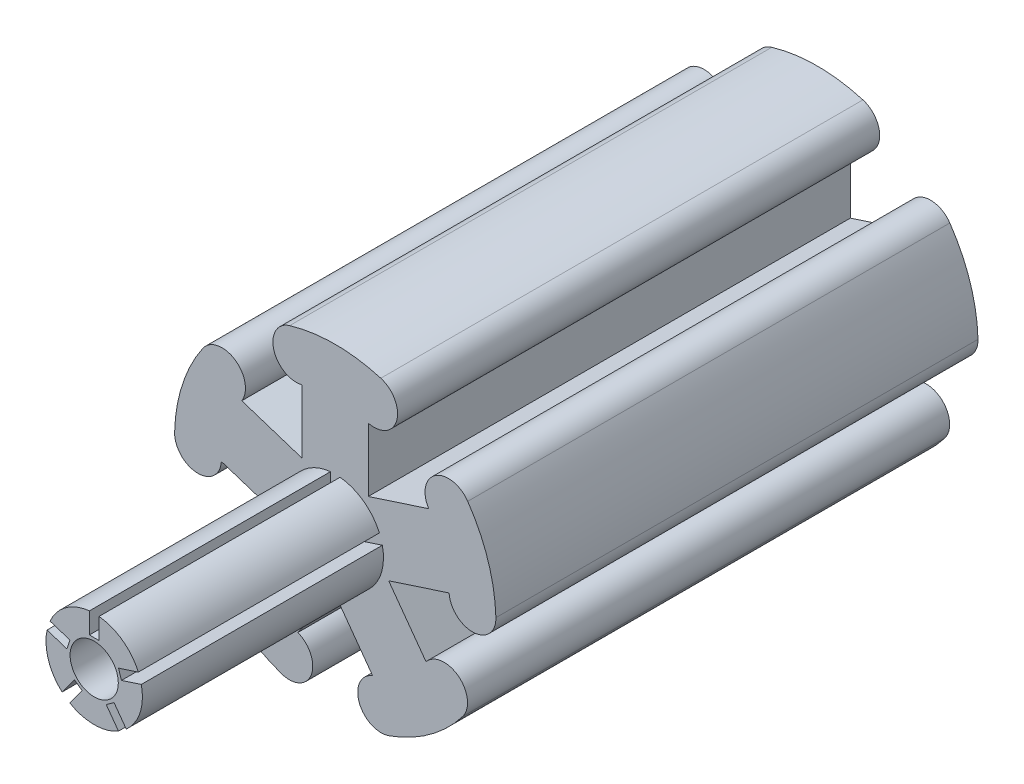
SolidWorks part; units mm, degrees
ref_plane "Front Plane" through (0, 0, 0) normal (0, 0, 1) x (1, 0, 0)
ref_plane "Top Plane" through (0, 0, 0) normal (0, 1, 0) x (1, 0, 0)
ref_plane "Right Plane" through (0, 0, 0) normal (1, 0, 0) x (0, 0, -1)
sketch "Sketch2" plane through (0, 0, 0) normal (0, 0, 1) x (1, 0, 0)
  line L9 (-2.054, 0) -> (2.054, 0)
  line L10 (-2.054, 0) -> (-2.054, 9.7868)
  line L11 (-2.054, 9.7868) -> (2.054, 9.7868)
  line L12 (2.054, 0) -> (2.054, 9.7868)
  circle A5 centre (0, 0) radius 10
  arc A6 (2.4222, 8.1926) -> (-2.4222, 8.1926) centre (0, 0) ccw construction
  arc A7 (2.8353, 9.5896) -> (-2.8353, 9.5896) centre (0, 0) ccw
  arc A8 (2.0092, 6.7955) -> (-2.0092, 6.7955) centre (0, 0) ccw
  arc A9 (2.0092, 6.7955) -> (2.8353, 9.5896) centre (2.4222, 8.1926) ccw
  arc A10 (-2.8353, 9.5896) -> (-2.0092, 6.7955) centre (-2.4222, 8.1926) ccw
  point P8 (0, 8.5432)
  dimension "D1" = 20
extrude "Boss-Extrude3" add sketch "Sketch2" against normal blind 30
sketch "Sketch5" plane through (0, 0, 0) normal (1, 0, 0) x (0, 0, -1)
  line L0 (0, 0) -> (12.727, 0)
pattern_circular "CirPattern1" count 5 over 360 about axis through (0, 0, 0) along (0, 0, 1) of "Boss-Extrude3"
sketch "Sketch7" plane through (0, 0, 0) normal (0, 0, 1) x (1, 0, 0)
  line L1 (0.3, 1.6874) -> (-0.3, 1.6874)
  line L2 (0.3, 1.6874) -> (0.3, 2.985)
  line L3 (0.3, 2.985) -> (-0.3, 2.985)
  line L4 (-0.3, 1.6874) -> (-0.3, 2.985)
  line L11 (-4.587, -2.3019) -> (-4.287, -2.8215)
  line L18 (2.9316, 0.6371) -> (2.7462, 1.2077)
  line L19 (1.6975, 0.2361) -> (2.9316, 0.6371)
  line L20 (1.6975, 0.2361) -> (1.5121, 0.8067)
  line L21 (1.5121, 0.8067) -> (2.7462, 1.2077)
  line L22 (1.5118, -2.5912) -> (1.9972, -2.2385)
  line L23 (0.7491, -1.5415) -> (1.5118, -2.5912)
  line L24 (0.7491, -1.5415) -> (1.2345, -1.1888)
  line L25 (1.2345, -1.1888) -> (1.9972, -2.2385)
  line L26 (-1.9972, -2.2385) -> (-1.5118, -2.5912)
  line L27 (-1.2345, -1.1888) -> (-1.9972, -2.2385)
  line L28 (-1.2345, -1.1888) -> (-0.7491, -1.5415)
  line L29 (-0.7491, -1.5415) -> (-1.5118, -2.5912)
  line L30 (-2.7462, 1.2077) -> (-2.9316, 0.6371)
  line L31 (-1.5121, 0.8067) -> (-2.7462, 1.2077)
  line L32 (-1.5121, 0.8067) -> (-1.6975, 0.2361)
  line L33 (-1.6975, 0.2361) -> (-2.9316, 0.6371)
  circle A0 centre (0, 0) radius 3
  point P7 (0, 1.6874)
  point P18 (0, 0)
  point P43 (0, 0)
  dimension "D2" = 5
  dimension "D3" = 0.6
extrude "Boss-Extrude4" add sketch "Sketch7" along normal blind 15
sketch "Sketch6" plane through (0, 0, -30) normal (0, 0, -1) x (-1, 0, 0)
  circle A0 centre (0, 0) radius 1.5
extrude "Cut-Extrude1" cut sketch "Sketch6" against normal blind 80
